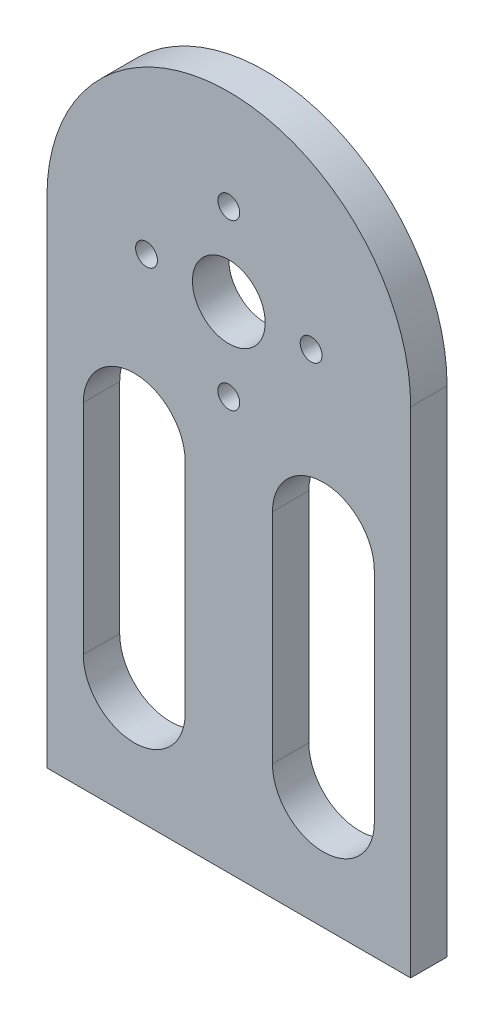
SolidWorks part; units mm, degrees
ref_plane "Płaszczyzna przednia" through (0, 0, 0) normal (0, 0, 1) x (1, 0, 0)
ref_plane "Płaszczyzna górna" through (0, 0, 0) normal (0, 1, 0) x (1, 0, 0)
ref_plane "Płaszczyzna prawa" through (0, 0, 0) normal (1, 0, 0) x (0, 0, -1)
sketch "Szkic1" plane through (0, 0, 0) normal (0, 0, 1) x (1, 0, 0)
  line L0 (0, 0) -> (0, 46.5) construction
  line L1 (-12.5, 34) -> (-12.5, 0)
  line L2 (-12.5, 0) -> (12.5, 0)
  line L3 (-6.5, 23) -> (-6.5, 8) construction
  line L4 (-3, 23) -> (-3, 8)
  line L5 (-10, 23) -> (-10, 8)
  line L6 (12.5, 34) -> (12.5, 0)
  line L7 (6.5, 23) -> (6.5, 8) construction
  line L8 (3, 23) -> (3, 8)
  line L9 (10, 23) -> (10, 8)
  arc A0 (12.5, 34) -> (-12.5, 34) centre (0, 34) ccw
  arc A1 (-3, 23) -> (-10, 23) centre (-6.5, 23) ccw
  arc A2 (-10, 8) -> (-3, 8) centre (-6.5, 8) ccw
  circle A3 centre (0, 34) radius 2.5
  circle A4 centre (0, 39.6569) radius 0.75
  circle A5 centre (5.6569, 34) radius 0.75
  circle A6 centre (0, 28.3431) radius 0.75
  circle A7 centre (-5.6569, 34) radius 0.75
  arc A8 (3, 23) -> (10, 23) centre (6.5, 23) cw
  arc A9 (10, 8) -> (3, 8) centre (6.5, 8) cw
  point P9 (-6.5, 15.5)
  point P15 (-6.5, 26.5)
  point P16 (-6.5, 4.5)
  point P17 (0, 0)
  point P18 (-10, 15.5)
  point P30 (0, 34)
  point P33 (6.5, 15.5)
  dimension "D2" = 25
  dimension "D3" = 5
  dimension "D5" = 22
  dimension "D8" = 1.5
  dimension "D10" = 8
  dimension "D1" = 46.5
  dimension "D4" = 7
  dimension "D6" = 4.5
  dimension "D7" = 2.5
  dimension "D9" = 4
extrude "Dodanie-wyciągnięcie1" add sketch "Szkic1" along normal blind 2.5
